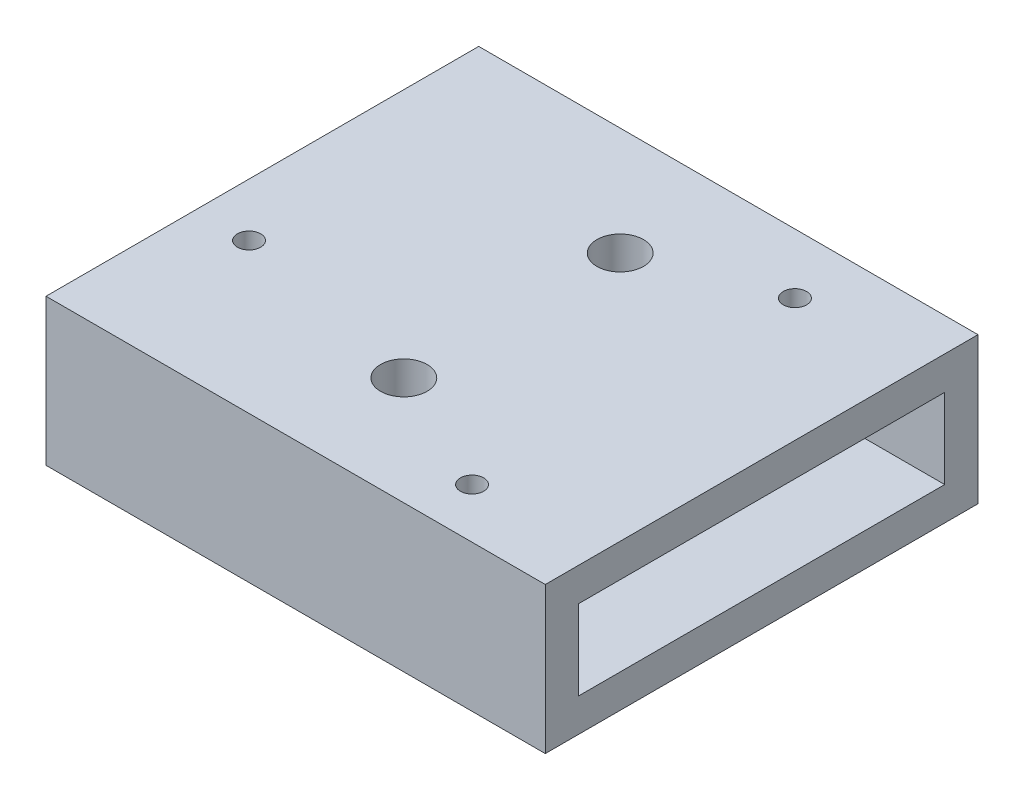
SolidWorks part; units mm, degrees
ref_plane "Front Plane" through (0, 0, 0) normal (0, 0, 1) x (1, 0, 0)
ref_plane "Top Plane" through (0, 0, 0) normal (0, 1, 0) x (1, 0, 0)
ref_plane "Right Plane" through (0, 0, 0) normal (1, 0, 0) x (0, 0, -1)
sketch "Sketch1" plane through (0, 0, 0) normal (0, 1, 0) x (1, 0, 0)
  line L1 (37.5, 32.5) -> (-37.5, 32.5)
  line L2 (37.5, 32.5) -> (37.5, -32.5)
  line L3 (37.5, -32.5) -> (-37.5, -32.5)
  line L4 (-37.5, 32.5) -> (-37.5, -32.5)
  line L5 (37.5, 32.5) -> (-37.5, -32.5) construction
  line L6 (37.5, -32.5) -> (-37.5, 32.5) construction
  point P0 (0, 0)
extrude "Boss-Extrude1" add sketch "Sketch1" along normal blind 22
sketch "Sketch2" plane through (37.5, 0, 0) normal (1, 0, 0) x (0, 0, -1)
  line L1 (-27.5, 17) -> (27.5, 17)
  line L2 (-27.5, 17) -> (-27.5, 5)
  line L3 (-27.5, 5) -> (27.5, 5)
  line L4 (27.5, 17) -> (27.5, 5)
  line L5 (-27.5, 17) -> (27.5, 5) construction
  line L6 (-27.5, 5) -> (27.5, 17) construction
  point P0 (0, 11)
extrude "Cut-Extrude1" cut sketch "Sketch2" against normal blind 70
sketch "Sketch3" plane through (-37.5, 0, 0) normal (-1, 0, 0) x (0, 0, 1)
  line L1 (-24.5, 17) -> (-9.5, 17)
  line L2 (-24.5, 17) -> (-24.5, 5)
  line L3 (-24.5, 5) -> (-9.5, 5)
  line L4 (-9.5, 17) -> (-9.5, 5)
  line L5 (-24.5, 17) -> (-9.5, 5) construction
  line L6 (-24.5, 5) -> (-9.5, 17) construction
  point P0 (-17, 11)
extrude "Cut-Extrude2" cut sketch "Sketch3" against normal through all
sketch "Sketch4" plane through (0, 22, 0) normal (0, 1, 0) x (1, 0, 0)
  circle A0 centre (19, -25) radius 1.75
extrude "Cut-Extrude3" cut sketch "Sketch4" against normal through all
sketch "Sketch7" plane through (0, 22, 0) normal (0, 1, 0) x (1, 0, 0)
  circle A0 centre (19, 23.5) radius 1.75
extrude "Cut-Extrude5" cut sketch "Sketch7" against normal through all
sketch "Sketch8" plane through (0, 22, 0) normal (0, 1, 0) x (1, 0, 0)
  circle A0 centre (-29.5, -10) radius 1.75
extrude "Cut-Extrude6" cut sketch "Sketch8" against normal through all
sketch "Sketch9" plane through (0, 22, 0) normal (0, 1, 0) x (1, 0, 0)
  circle A0 centre (0, -16.25) radius 3.5
extrude "Cut-Extrude7" cut sketch "Sketch9" against normal blind 6
sketch "Sketch10" plane through (0, 22, 0) normal (0, 1, 0) x (1, 0, 0)
  circle A0 centre (0, 16.25) radius 3.5
extrude "Cut-Extrude8" cut sketch "Sketch10" against normal blind 6
